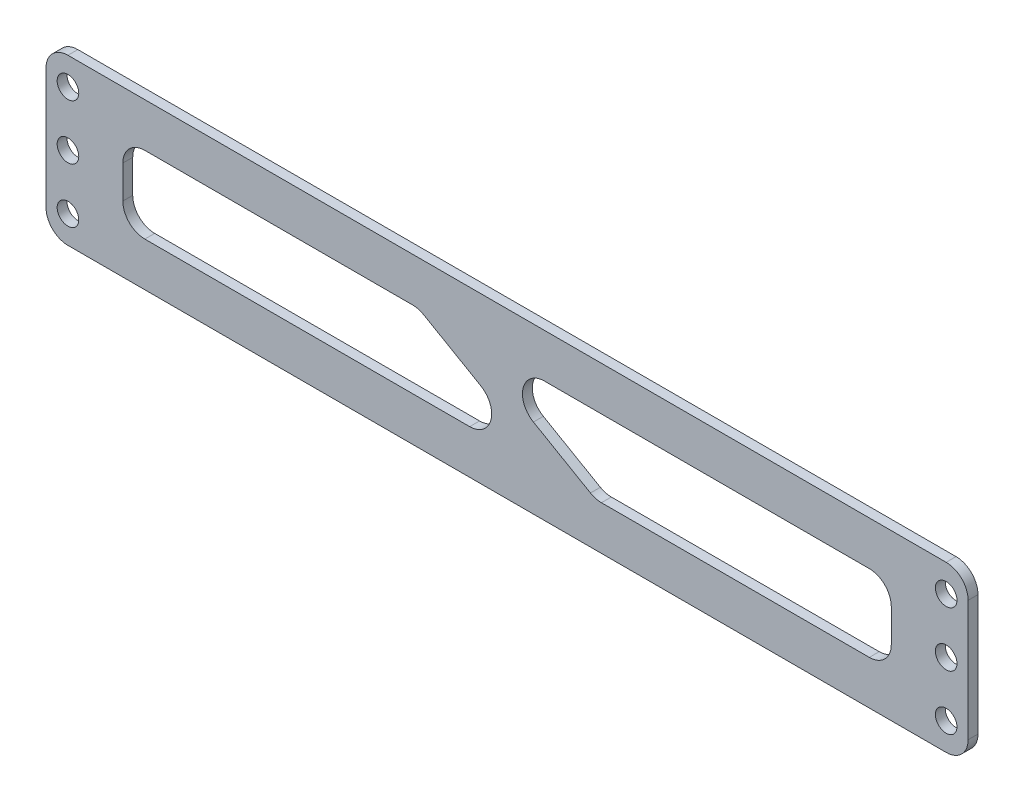
SolidWorks part; units mm, degrees
material "6061-T6 (SS)"
ref_plane "Front Plane" through (0, 0, 0) normal (0, 0, 1) x (1, 0, 0)
ref_plane "Top Plane" through (0, 0, 0) normal (0, 1, 0) x (1, 0, 0)
ref_plane "Right Plane" through (0, 0, 0) normal (1, 0, 0) x (0, 0, -1)
sketch "Sketch1" plane through (0, 0, 0) normal (0, 0, 1) x (1, 0, 0)
  line L1 (-12.7, 774.7) -> (49987.3, 774.7) construction
  line L2 (-7.62, 368.3) -> (210.82, 368.3) construction
  line L3 (-12.7, 1181.1) -> (-12.7, 368.3) construction
  line L4 (-7.62, 755.65) -> (210.82, 755.65)
  line L5 (-12.7, 760.73) -> (-12.7, 788.67)
  line L6 (-7.62, 793.75) -> (210.82, 793.75)
  line L7 (215.9, 760.73) -> (215.9, 788.67)
  line L8 (215.9, 1181.1) -> (215.9, 368.3) construction
  line L9 (17.78, 783.59) -> (79.7609, 783.59)
  line L10 (12.7, 1181.1) -> (12.7, 368.3) construction
  line L11 (190.5, 1181.1) -> (190.5, 368.3) construction
  line L12 (190.5, 778.51) -> (190.5, 770.89)
  line L13 (185.42, 765.81) -> (123.4391, 765.81)
  line L14 (12.7, 770.89) -> (12.7, 778.51)
  line L15 (82.3009, 782.9094) -> (95.4991, 775.2894)
  line L16 (107.7009, 774.1106) -> (120.8991, 766.4906)
  line L17 (81.1221, 783.59) -> (81.1221, -49216.41) construction
  line L18 (122.0779, 765.81) -> (122.0779, 50765.81) construction
  line L19 (101.6, 765.81) -> (101.6, 50765.81) construction
  line L20 (110.2409, 783.59) -> (185.42, 783.59)
  line L21 (92.9591, 765.81) -> (17.78, 765.81)
  arc A0 (210.82, 793.75) -> (215.9, 788.67) centre (210.82, 788.67) cw
  arc A1 (210.82, 755.65) -> (215.9, 760.73) centre (210.82, 760.73) ccw
  arc A2 (-12.7, 788.67) -> (-7.62, 793.75) centre (-7.62, 788.67) cw
  arc A3 (-7.62, 755.65) -> (-12.7, 760.73) centre (-7.62, 760.73) cw
  circle A4 centre (0, 762) radius 2.5
  circle A5 centre (0, 774.7) radius 2.5
  circle A6 centre (0, 787.4) radius 2.5
  circle A7 centre (203.2, 762) radius 2.5
  circle A8 centre (203.2, 774.7) radius 2.5
  circle A9 centre (203.2, 787.4) radius 2.5
  arc A10 (185.42, 783.59) -> (190.5, 778.51) centre (185.42, 778.51) cw
  arc A11 (190.5, 770.89) -> (185.42, 765.81) centre (185.42, 770.89) cw
  arc A12 (17.78, 765.81) -> (12.7, 770.89) centre (17.78, 770.89) cw
  arc A13 (17.78, 783.59) -> (12.7, 778.51) centre (17.78, 778.51) ccw
  arc A14 (120.8991, 766.4906) -> (123.4391, 765.81) centre (123.4391, 770.89) ccw
  arc A15 (107.7009, 774.1106) -> (110.2409, 783.59) centre (110.2409, 778.51) cw
  arc A16 (82.3009, 782.9094) -> (79.7609, 783.59) centre (79.7609, 778.51) ccw
  arc A17 (95.4991, 775.2894) -> (92.9591, 765.81) centre (92.9591, 770.89) cw
  point P14 (215.9, 793.75)
  point P17 (215.9, 755.65)
  point P22 (-12.7, 755.65)
  point P55 (190.5, 783.59)
  point P58 (190.5, 765.81)
  point P61 (12.7, 765.81)
  point P64 (12.7, 783.59)
  point P73 (122.0779, 765.81)
  point P76 (91.2821, 783.59)
  point P79 (81.1221, 783.59)
  point P82 (111.9179, 765.81)
  dimension "D4" = 5.08
  dimension "D7" = 5.08
  dimension "D12" = 5.08
  dimension "D1" = 406.4
  dimension "D2" = 38.1
  dimension "D3" = 19.05
  dimension "D5" = 10.16
  dimension "D6" = 10.16
  dimension "D8" = 5.08
  dimension "D9" = 30
  dimension "D10" = 20.4779
  dimension "D11" = 88.9
extrude "Boss-Extrude1" add sketch "Sketch1" along normal blind 2.286
sketch "Sketch2" [suppressed] plane through (0, 0, 0) normal (0, 0, 1) x (1, 0, 0)
  circle A0 centre (27.1191, 775.0388) radius 2.54
  circle A1 centre (68.5634, 775.0388) radius 2.54
  circle A2 centre (133.0475, 775.0388) radius 2.54
  circle A3 centre (171.352, 775.0388) radius 2.54
  dimension "D1" = 5.08
sketch "Sketch3" plane through (0, 0, 0) normal (0, 0, -1) x (-1, 0, 0)
  line L0 (7.62, 755.65) -> (-210.82, 755.65) construction
  line L1 (-208.28, 755.65) -> (5.08, 755.65)
  line L2 (-208.28, 755.65) -> (-208.28, 793.75)
  line L3 (-208.28, 793.75) -> (5.08, 793.75)
  line L4 (5.08, 755.65) -> (5.08, 793.75)
  line L5 (-210.82, 793.75) -> (7.62, 793.75) construction
  line L6 (-215.9, 760.73) -> (-215.9, 788.67) construction
  line L7 (12.7, 788.67) -> (12.7, 760.73) construction
  line L12 (-215.9, 788.67) -> (-215.9, 760.73)
  line L13 (-210.82, 755.65) -> (7.62, 755.65)
  line L14 (12.7, 760.73) -> (12.7, 788.67)
  line L15 (7.62, 793.75) -> (-210.82, 793.75)
  line L16 (-215.9, 788.67) -> (-215.9, 760.73)
  line L17 (-210.82, 755.65) -> (7.62, 755.65)
  line L18 (12.7, 760.73) -> (12.7, 788.67)
  line L19 (7.62, 793.75) -> (-210.82, 793.75)
  arc A4 (-210.82, 793.75) -> (-215.9, 788.67) centre (-210.82, 788.67) ccw
  arc A5 (-215.9, 760.73) -> (-210.82, 755.65) centre (-210.82, 760.73) ccw
  arc A6 (7.62, 755.65) -> (12.7, 760.73) centre (7.62, 760.73) ccw
  arc A7 (12.7, 788.67) -> (7.62, 793.75) centre (7.62, 788.67) ccw
  arc A8 (-210.82, 793.75) -> (-215.9, 788.67) centre (-210.82, 788.67) ccw
  arc A9 (-215.9, 760.73) -> (-210.82, 755.65) centre (-210.82, 760.73) ccw
  arc A10 (7.62, 755.65) -> (12.7, 760.73) centre (7.62, 760.73) ccw
  arc A11 (12.7, 788.67) -> (7.62, 793.75) centre (7.62, 788.67) ccw
  arc M14 (-210.82, 793.75) -> (-215.9, 788.67) centre (-210.82, 788.67) ccw
  line M15 (-215.9, 788.67) -> (-215.9, 760.73)
  arc M16 (-215.9, 760.73) -> (-210.82, 755.65) centre (-210.82, 760.73) ccw
  line M17 (-210.82, 755.65) -> (7.62, 755.65)
  arc M18 (7.62, 755.65) -> (12.7, 760.73) centre (7.62, 760.73) ccw
  line M19 (12.7, 760.73) -> (12.7, 788.67)
  arc M20 (12.7, 788.67) -> (7.62, 793.75) centre (7.62, 788.67) ccw
  line M21 (7.62, 793.75) -> (-210.82, 793.75)
  dimension "D1" = 7.62
  dimension "D2" = 7.62
  dimension "D3" = 0
extrude "Cut-Extrude1" cut sketch "Sketch3" against normal through all contours L2 M17 M21 M14 M15 M16 | L4 M17 M18 M19 M20 M21
fillet "Fillet1" radius 5.08 4 edges at (-5.08, 755.65, 1.143) (-5.08, 793.75, 1.143) (208.28, 755.65, 1.143) (208.28, 793.75, 1.143)
